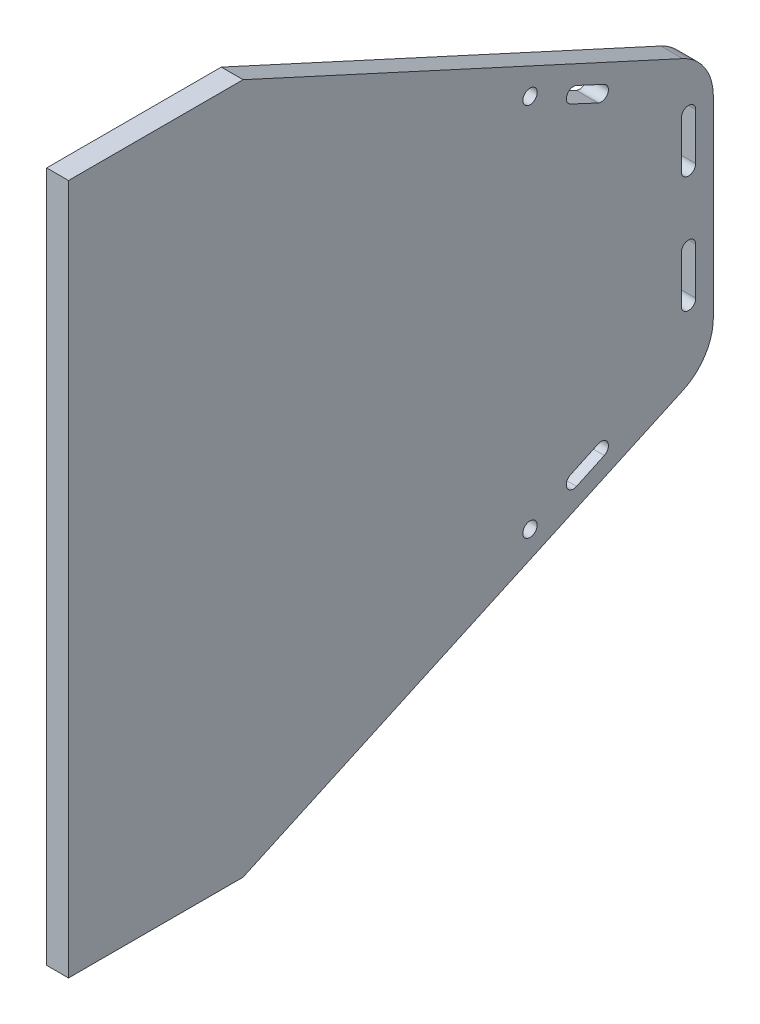
SolidWorks part; units mm, degrees
ref_plane "Front Plane" through (0, 0, 0) normal (0, 0, 1) x (1, 0, 0)
ref_plane "Top Plane" through (0, 0, 0) normal (0, 1, 0) x (1, 0, 0)
ref_plane "Right Plane" through (0, 0, 0) normal (1, 0, 0) x (0, 0, -1)
sketch "Sketch1" plane through (0, 0, 0) normal (1, 0, 0) x (0, 0, -1)
  line L0 (-44.0405, 114.8904) -> (-44.0405, -43.3296)
  line L1 (-44.0405, -43.3296) -> (-4.0405, -43.3296)
  line L2 (-4.0405, -43.3296) -> (96.6793, 2.8472)
  line L3 (103.6782, 13.7554) -> (103.6782, 57.8054)
  line L4 (96.6793, 68.7136) -> (-4.0405, 114.8904)
  line L5 (-4.0405, 114.8904) -> (-44.0405, 114.8904)
  line L6 (96.6793, 54.6272) -> (96.6793, 43.9272) construction
  line L7 (98.3293, 54.6272) -> (98.3293, 43.9272)
  line L8 (95.0293, 54.6272) -> (95.0293, 43.9272)
  line L9 (96.6793, 27.9272) -> (96.6793, 17.2272) construction
  line L10 (98.3293, 27.9272) -> (98.3293, 17.2272)
  line L11 (95.0293, 27.9272) -> (95.0293, 17.2272)
  line L12 (191.0018, -40.0871) -> (191.0018, -50.7871) construction
  line L13 (192.6518, -40.0871) -> (192.6518, -50.7871)
  line L14 (189.3518, -40.0871) -> (189.3518, -50.7871)
  line L15 (191.0018, -66.7871) -> (191.0018, -77.4871) construction
  line L16 (192.6518, -66.7871) -> (192.6518, -77.4871)
  line L17 (189.3518, -66.7871) -> (189.3518, -77.4871)
  arc A0 (96.6793, 2.8472) -> (103.6782, 13.7554) centre (91.6782, 13.7554) ccw
  arc A1 (103.6782, 57.8054) -> (96.6793, 68.7136) centre (91.6782, 57.8054) ccw
  arc A2 (98.3293, 54.6272) -> (95.0293, 54.6272) centre (96.6793, 54.6272) ccw
  arc A3 (95.0293, 43.9272) -> (98.3293, 43.9272) centre (96.6793, 43.9272) ccw
  arc A4 (98.3293, 27.9272) -> (95.0293, 27.9272) centre (96.6793, 27.9272) ccw
  arc A5 (95.0293, 17.2272) -> (98.3293, 17.2272) centre (96.6793, 17.2272) ccw
  circle A6 centre (59.3269, -8.1722) radius 1.65
  circle A7 centre (59.1754, 79.8024) radius 1.65
  circle A8 centre (153.6494, -102.8865) radius 1.65
  circle A9 centre (153.498, -14.9118) radius 1.65
  arc A10 (192.6518, -40.0871) -> (189.3518, -40.0871) centre (191.0018, -40.0871) ccw
  arc A11 (189.3518, -50.7871) -> (192.6518, -50.7871) centre (191.0018, -50.7871) ccw
  arc A12 (192.6518, -66.7871) -> (189.3518, -66.7871) centre (191.0018, -66.7871) ccw
  arc A13 (189.3518, -77.4871) -> (192.6518, -77.4871) centre (191.0018, -77.4871) ccw
  point P9 (103.6782, 6.056)
  point P11 (103.6782, 65.5048)
  point P14 (96.6793, 49.2772)
  point P19 (96.6793, 22.5772)
  point P35 (191.0018, -45.4371)
  point P40 (191.0018, -72.1371)
  dimension "D7" = 12
  dimension "D8" = 12
  dimension "D10" = 1.65
  dimension "D11" = 1.65
  dimension "D15" = 3.3
  dimension "D16" = 3.3
  dimension "D17" = 45.17
  dimension "D1" = 44.05
  dimension "D2" = 158.22
  dimension "D3" = 118.5
  dimension "D4" = 40
  dimension "D5" = 118.5
  dimension "D6" = 40
  dimension "D9" = 16
  dimension "D12" = 14.38
  dimension "D13" = 10.7
  dimension "D14" = 10.7
  dimension "D18" = 5.55
  dimension "D19" = 5.55
  dimension "D20" = 45.17
extrude "Boss-Extrude1" add sketch "Sketch1" along normal blind 5 contours L3 A1 L4 L5 L0 L1 L2 A0
sketch "Sketch4" plane through (5, 0, 0) normal (1, 0, 0) x (0, 0, -1)
  line L0 (97.9971, 57.1195) -> (97.9971, 46.4195) construction
  line L1 (99.6471, 57.1195) -> (99.6471, 46.4195)
  line L2 (96.3471, 57.1195) -> (96.3471, 46.4195)
  line L3 (97.9971, 30.4195) -> (97.9971, 19.7195) construction
  line L4 (99.6471, 30.4195) -> (99.6471, 19.7195)
  line L5 (96.3471, 30.4195) -> (96.3471, 19.7195)
  line L6 (-4.0405, -43.3296) -> (96.6793, 2.8472) construction
  line L7 (71.6533, 74.0559) -> (77.9968, 71.0962) construction
  line L8 (-896.3218, 35.7804) -> (49103.6782, 35.7804) construction
  line L11 (71.6533, -2.4951) -> (77.9968, 0.4647) construction
  line L12 (70.9557, -0.9998) -> (77.2992, 1.9599)
  line L13 (72.351, -3.9903) -> (78.6945, -1.0306)
  line L14 (101.5052, 11.4332) -> (-45209.1958, -21129.5311) construction
  line L15 (103.6782, 13.7554) -> (103.6782, 57.8054) construction
  line L16 (70.9557, 72.5607) -> (77.2992, 69.6009)
  line L17 (72.351, 75.5512) -> (78.6945, 72.5914)
  arc A0 (99.6471, 57.1195) -> (96.3471, 57.1195) centre (97.9971, 57.1195) ccw
  arc A1 (96.3471, 46.4195) -> (99.6471, 46.4195) centre (97.9971, 46.4195) ccw
  arc A2 (99.6471, 30.4195) -> (96.3471, 30.4195) centre (97.9971, 30.4195) ccw
  arc A3 (96.3471, 19.7195) -> (99.6471, 19.7195) centre (97.9971, 19.7195) ccw
  circle A5 centre (61.685, -7.1461) radius 1.65
  arc A8 (70.9557, -0.9998) -> (72.351, -3.9903) centre (71.6533, -2.4951) ccw
  arc A9 (78.6945, -1.0306) -> (77.2992, 1.9599) centre (77.9968, 0.4647) ccw
  arc A10 (70.9557, 72.5607) -> (72.351, 75.5512) centre (71.6533, 74.0559) cw
  arc A11 (78.6945, 72.5914) -> (77.2992, 69.6009) centre (77.9968, 71.0962) cw
  circle A12 centre (61.685, 78.7069) radius 1.65
  point P2 (97.9971, 51.7695)
  point P7 (97.9971, 25.0695)
  point P25 (103.6782, 35.7804)
  point P27 (74.8251, 72.576)
  point P29 (74.8251, -1.0152)
  dimension "D3" = 1.65
  dimension "D4" = 1.65
  dimension "D6" = 3.3
  dimension "D14" = 1.65
  dimension "D1" = 10.7
  dimension "D2" = 10.7
  dimension "D5" = 16
  dimension "D8" = 5.5
  dimension "D11" = 45.17
  dimension "D12" = 5
  dimension "D15" = 7
  dimension "D16" = 11
extrude "Cut-Extrude1" cut sketch "Sketch4" against normal blind 5
